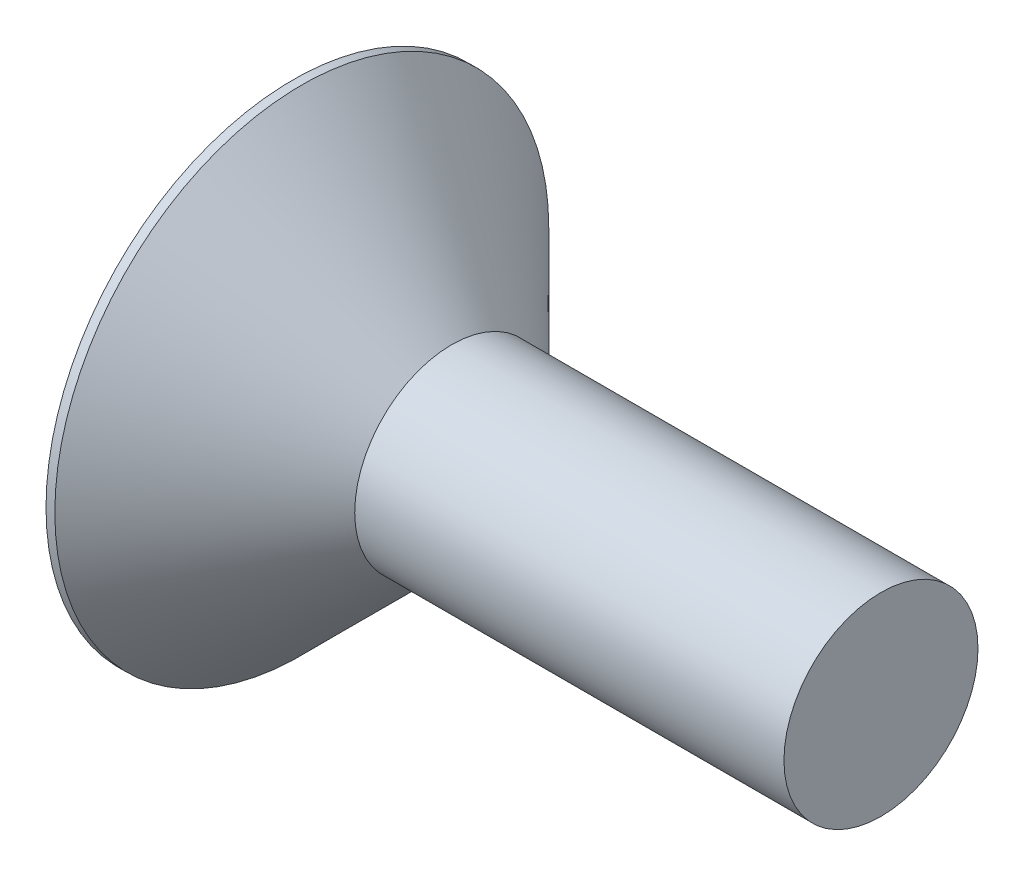
SolidWorks part; units mm, degrees
revolve "Base-Revolve" add sketch "BodySke"
sketch "BodySke" plane through (0, 0, 0) normal (0, 0, 1) x (1, 0, 0)
  line L0 (0, 0) -> (0, 4.2)
  line L1 (0, 4.2) -> (0.15, 4.2)
  line L2 (2.7, 1.65) -> (10, 1.65)
  line L3 (10, 1.65) -> (10, 0)
  line L4 (10, 0) -> (0, 0)
  line L5 (-6.35, 0) -> (82.55, 0) construction
  line L6 (2.7, -1.65) -> (10, -1.65) construction
  line L7 (0.15, -4.2) -> (2.7, -1.65) construction
  line L8 (0.15, 4.2) -> (2.7, 1.65)
  line L9 (0, -4.2) -> (0.15, -4.2) construction
  line L10 (3.4, 3.2375) -> (3.4, -6.2875) construction
  line L11 (0, 6.35) -> (0, -3.175) construction
  dimension "Diameter" = 3.3
  dimension "Length" = 10
  dimension "Head_ht" = 2.7
  dimension "Head_dia" = 8.4
  dimension "Head_ang" = 90
  dimension "D6" = 0.15
  dimension "Advance" = 0.7
  dimension "Thread_nom" = 10
cosmetic thread "ThreadCosmetic" [suppressed]
fillet "Fillet1" [suppressed] radius 1
ref_plane "Plane1" through (0, 0, 0) normal (0, 0, 1) x (1, 0, 0)
ref_plane "Plane2" through (0, 0, 0) normal (0, 1, 0) x (1, 0, 0)
ref_plane "Plane3" through (0, 0, 0) normal (1, 0, 0) x (0, 0, -1)
other "Configuration Table"
sketch "Sketch3" plane through (0, 0, 0) normal (-1, 0, 0) x (0, 0, 1)
  line L0 (-0.515, 2.2) -> (0.515, 2.2)
  line L1 (0.515, 2.2) -> (0.515, -2.2)
  line L2 (0.515, -2.2) -> (-0.515, -2.2)
  line L3 (-0.515, -2.2) -> (-0.515, 2.2)
  dimension "Cross_dia" = 4.4
  dimension "Cross_width" = 1.03
  dimension "D1" = 2.2
  dimension "D2" = 0.515
ref_plane "Plane4" through (2.51, 0, 0) normal (-1, 0, 0) x (0, 0, 1)
sketch "Sketch4" plane through (2.51, 0, 0) normal (-1, 0, 0) x (0, 0, 1)
  line L0 (-0.515, 0.9486) -> (0.515, 0.9486)
  line L3 (0.515, 0.9486) -> (0.515, -0.9486)
  line L4 (0.515, -0.9486) -> (-0.515, -0.9486)
  line L5 (-0.515, -0.9486) -> (-0.515, 0.9486)
  dimension "D2" = 1.8971
  dimension "D1" = 1.03
  dimension "D4" = 0.9486
  dimension "D3" = 0.515
loft "Recess" cut profiles "Sketch3", "Sketch4"
pattern_circular "RecPat" count 2 every 90 about axis through (0, 0, 0) along (1, 0, 0) of "Recess"
sketch "RecCorSke" plane through (0, 0, 0) normal (0, 0, 1) x (1, 0, 0)
  line L0 (-3.175, 0) -> (15.875, 0) construction
  line L2 (0, 0) -> (0, 1.0265)
  line L3 (0, 1.0265) -> (2.51, 0.851)
  line L4 (2.51, 0.851) -> (2.7865, 0)
  line L5 (2.7865, 0) -> (0, 0)
  dimension "Diameter" = 1.702
  dimension "Depth" = 2.51
  dimension "Draft_angle" = 4
  dimension "Bottom_angle" = 18
revolve "RecessCore" cut sketch "RecCorSke" angle 360 about L0
sketch "ThdSchSke" plane through (0, 0, 0) normal (0, 0, 1) x (1, 0, 0)
  line L0 (3.4, -1.61) -> (3.372, -1.65)
  line L1 (3.4, -1.61) -> (3.428, -1.65)
  line L2 (3.428, -1.65) -> (3.428, -2.0625)
  line L3 (-3.175, 0) -> (5.1513, 0) construction
  line L5 (3.428, -2.0625) -> (3.372, -2.0625)
  line L6 (3.372, -2.0625) -> (3.372, -1.65)
  line L7 (0, 4.2) -> (0, -4.2) construction
  dimension "Diameter" = 3.3
  dimension "Thread_minor" = 3.22
  dimension "Start" = 3.4
revolve "ThreadSchematic" [suppressed] cut sketch "ThdSchSke" angle 360 about L3
pattern_linear "ThdSchPat" [suppressed]
equation "\"D1@Sketch3\" = \"Cross_dia@Sketch3\" / 2"
equation "\"D2@Sketch3\" = \"Cross_width@Sketch3\" / 2"
equation "\"Depth@RecCorSke\" = \"Cross_depth@Plane4\""
equation "\"D1@Sketch4\" = \"Cross_width@Sketch3\""
equation "\"D2@Sketch4\" = \"Cross_dia@Sketch3\" - 2.0 * \"Cross_depth@Plane4\" * tan(26.5  * 0.017453292)"
equation "\"D3@Sketch4\" = \"D1@Sketch4\" / 2"
equation "\"D4@Sketch4\" = \"D2@Sketch4\" / 2"
equation "\"Thread_length@ThreadCosmetic\" = ((sgn( (\"Length@BodySke\" - \"Advance@BodySke\" * 1.0 - \"Head_ht@BodySke\" ) - \"Thread_nom@BodySke\" )-1)*( (\"Length@BodySke\" - \"Advance@BodySke\" * 1.0 - \"Head_ht@BodySke\" ) - \"Thread_nom@BodySke\" ))/-2+ \"Thread_nom@BodySke\""
equation "\"Thread_minor@ThdSchSke\" = \"Thread_minor@ThreadCosmetic\""
equation "\"Diameter@ThdSchSke\" = \"Diameter@BodySke\""
equation "\"Overcut@ThdSchSke\" = \"Diameter@BodySke\" * 1.25"
equation "\"Start@ThdSchSke\" = 0.000001 + \"Length@BodySke\" - \"Thread_length@ThreadCosmetic\"  '---Countersunk---"
equation "\"Num_threads@ThdSchPat\" = int( \"Thread_length@ThreadCosmetic\" / \"Advance@BodySke\" + 0.999 )  + 1"
equation "\"Advance@ThdSchPat\" = \"Thread_length@ThreadCosmetic\" /  (\"Num_threads@ThdSchPat\" - 1) 'relax it"
